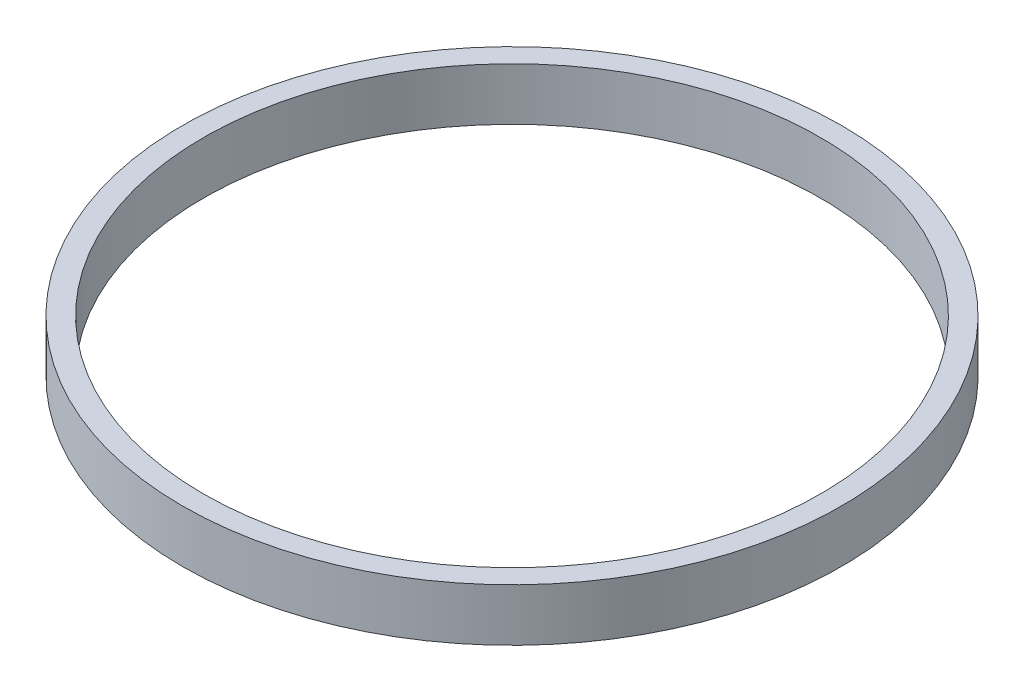
SolidWorks part; units mm, degrees
material "Epoxy, Unfilled"
ref_plane "Front Plane" through (0, 0, 0) normal (0, 0, 1) x (1, 0, 0)
ref_plane "Top Plane" through (0, 0, 0) normal (0, 1, 0) x (1, 0, 0)
ref_plane "Right Plane" through (0, 0, 0) normal (1, 0, 0) x (0, 0, -1)
sketch "Sketch1" plane through (0, 0, 0) normal (0, 1, 0) x (0.9999, 0, 0.016)
  circle A0 centre (4.0023, 4.8181) radius 58.838
  circle A2 centre (4.0023, 4.8181) radius 62.833
extrude "Boss-Extrude1" add sketch "Sketch1" along normal blind 10
